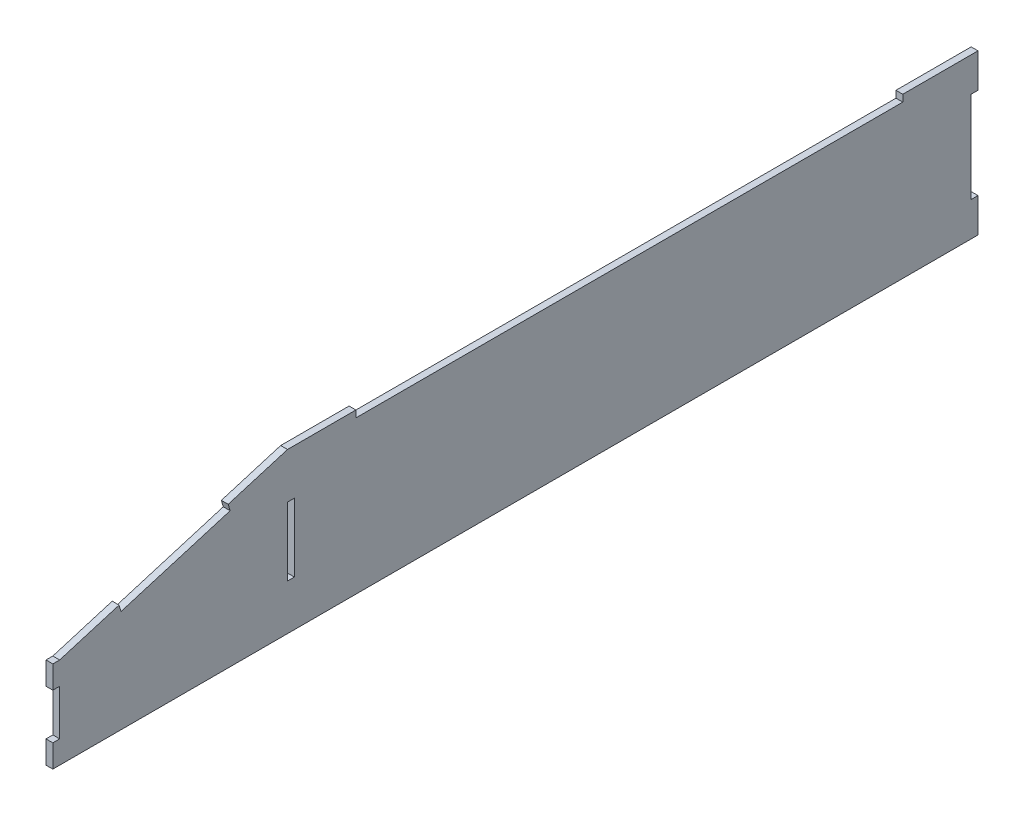
SolidWorks part; units mm, degrees
ref_plane "Front Plane" through (0, 0, 0) normal (0, 0, 1) x (1, 0, 0)
ref_plane "Top Plane" through (0, 0, 0) normal (0, 1, 0) x (1, 0, 0)
ref_plane "Right Plane" through (0, 0, 0) normal (1, 0, 0) x (0, 0, -1)
sketch "Sketch1" plane through (0, 0, 0) normal (1, 0, 0) x (0, 0, -1)
  line L0 (286.1443, 0.1739) -> (286.1443, 70.1739)
  line L1 (-16.8557, 70.1739) -> (286.1443, 70.1739)
  line L6 (-119.8557, 40.1739) -> (-116.8557, 40.1739)
  line L7 (-116.8557, 40.1739) -> (-16.8557, 70.1739)
  line L11 (-119.8557, 40.1739) -> (-119.8557, 0.1739)
  line L12 (-119.8557, 0.1739) -> (286.1443, 0.1739)
  dimension "D1" = 406
  dimension "D2" = 303
  dimension "D4" = 3
  dimension "D6" = 70
  dimension "D7" = 40
extrude "Boss-Extrude1" add sketch "Sketch1" along normal blind 3
sketch "Sketch5" plane through (3, 0, 0) normal (1, 0, 0) x (0, 0, -1)
  line L0 (286.1443, 55.1739) -> (283.1443, 55.1739)
  line L1 (286.1443, 0.1739) -> (286.1443, 70.1739) construction
  line L2 (283.1443, 55.1739) -> (283.1443, 15.1739)
  line L3 (283.1443, 15.1739) -> (286.1443, 15.1739)
  line L4 (-119.8557, 0.1739) -> (286.1443, 0.1739) construction
  dimension "D1" = 3
  dimension "D2" = 40
  dimension "D3" = 15
extrude "Cut-Extrude2" cut sketch "Sketch5" against normal blind 3 and the other way through all
sketch "Sketch6" plane through (3, 0, 0) normal (1, 0, 0) x (0, 0, -1)
  line L0 (253.1443, 70.1739) -> (253.1443, 67.1739)
  line L1 (286.1443, 70.1739) -> (-16.8557, 70.1739) construction
  line L2 (253.1443, 67.1739) -> (13.1443, 67.1739)
  line L3 (13.1443, 67.1739) -> (13.1443, 70.1739)
  line L4 (286.1443, 55.1739) -> (286.1443, 70.1739) construction
  dimension "D1" = 3
  dimension "D2" = 240
  dimension "D3" = 33
extrude "Cut-Extrude6" cut sketch "Sketch6" against normal blind 3 and the other way through all flip side to cut
sketch "Sketch7" plane through (3, 0, 0) normal (1, 0, 0) x (0, 0, -1)
  line L0 (-42.9086, 62.358) -> (-42.0465, 59.4846)
  line L1 (-16.8557, 70.1739) -> (-116.8557, 40.1739) construction
  line L2 (-42.0465, 59.4846) -> (-89.9378, 45.1172)
  line L3 (-89.9378, 45.1172) -> (-90.7999, 47.9906)
  dimension "D1" = 3
  dimension "D2" = 50
  dimension "D3" = 27.2
  dimension "D4" = 27.2031
extrude "Cut-Extrude11" cut sketch "Sketch7" against normal blind 3 and the other way through all flip side to cut
sketch "Sketch8" plane through (3, 0, 0) normal (1, 0, 0) x (0, 0, -1)
  line L0 (-119.8557, 30.1739) -> (-116.8557, 30.1739)
  line L1 (-119.8557, 40.1739) -> (-119.8557, 0.1739) construction
  line L2 (-116.8557, 30.1739) -> (-116.8557, 10.1739)
  line L3 (-116.8557, 10.1739) -> (-119.8557, 10.1739)
  line L4 (-119.8557, 0.1739) -> (286.1443, 0.1739) construction
  dimension "D1" = 3
  dimension "D2" = 20
  dimension "D3" = 10
extrude "Cut-Extrude12" cut sketch "Sketch8" against normal blind 3 and the other way through all flip side to cut
sketch "Sketch9" plane through (3, 0, 0) normal (1, 0, 0) x (0, 0, -1)
  line L0 (-16.8557, 50.1739) -> (-16.8557, 20.1739)
  line L1 (-16.8557, 20.1739) -> (-13.8557, 20.1739)
  line L2 (-13.8557, 20.1739) -> (-13.8557, 50.1739)
  line L3 (-13.8557, 50.1739) -> (-16.8557, 50.1739)
  line L4 (-119.8557, 0.1739) -> (286.1443, 0.1739) construction
  dimension "D1" = 30
  dimension "D2" = 20
  dimension "D3" = 3
extrude "Cut-Extrude13" cut sketch "Sketch9" against normal blind 3
